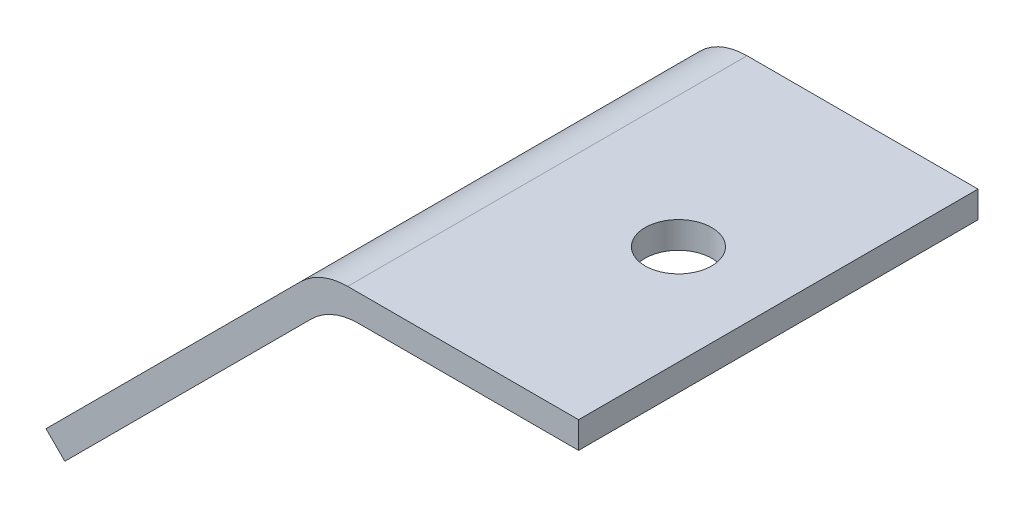
SolidWorks part; units mm, degrees
material "1023 Carbon Steel Sheet (SS)"
ref_plane "Front Plane" through (0, 0, 0) normal (0, 0, 1) x (1, 0, 0)
ref_plane "Top Plane" through (0, 0, 0) normal (0, 1, 0) x (1, 0, 0)
ref_plane "Right Plane" through (0, 0, 0) normal (1, 0, 0) x (0, 0, -1)
sketch "Sketch1" plane through (0, 0, 0) normal (0, 0, 1) x (1, 0, 0)
  line L0 (-86.359, -10) -> (-83.5305, -12.8284)
  line L1 (-83.5305, -12.8284) -> (-43.5305, 27.1716)
  line L2 (-43.5305, 27.1716) -> (-6.359, 27.1716)
  line L3 (-6.359, 27.1716) -> (-6.359, 31.1716)
  line L4 (-6.359, 31.1716) -> (-45.1874, 31.1716)
  line L5 (-45.1874, 31.1716) -> (-86.359, -10)
  dimension "D1" = 4
  dimension "D2" = 4
  dimension "D3" = 80
  dimension "D4" = 40
extrude "Boss-Extrude1" add sketch "Sketch1" along normal blind 60
fillet "Fillet1" radius 10 2 edges at (-43.5305, 27.1716, 30) (-45.1874, 31.1716, 30)
sketch "Sketch2" plane through (0, 31.1716, 0) normal (0, 1, 0) x (1, 0, 0)
  line L0 (-6.359, -60) -> (-6.359, 0) construction
  line L2 (-6.359, -60) -> (-41.0453, -60) construction
  line L3 (-30.7575, -60) -> (-30.7575, -30) construction
  line L4 (-30.7575, -30) -> (28.7897, -30) construction
  circle A0 centre (-21.359, -30) radius 5
  dimension "D1" = 10
  dimension "D2" = 30
  dimension "D3" = 15
extrude "Cut-Extrude1" cut sketch "Sketch2" against normal blind 60
